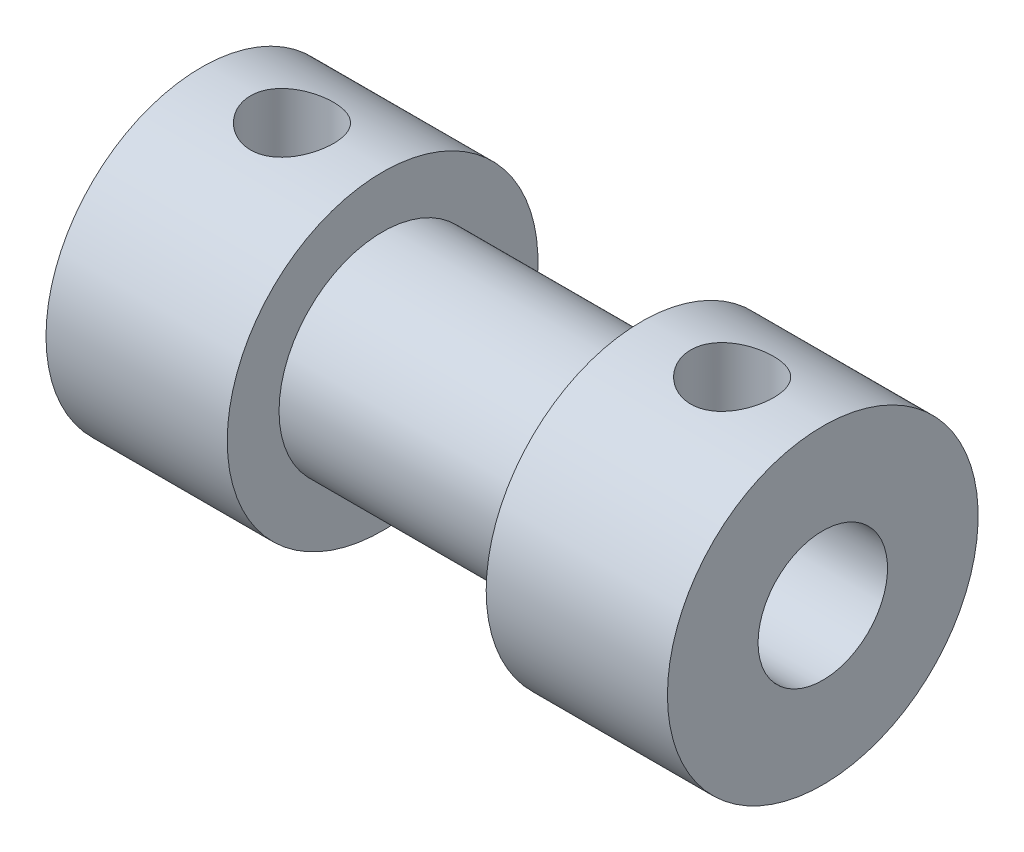
SolidWorks part; units mm, degrees
material "ABS"
ref_plane "Front Plane" through (0, 0, 0) normal (0, 0, 1) x (1, 0, 0)
ref_plane "Top Plane" through (0, 0, 0) normal (0, 1, 0) x (1, 0, 0)
ref_plane "Right Plane" through (0, 0, 0) normal (1, 0, 0) x (0, 0, -1)
sketch "Sketch1" plane through (0, 0, 0) normal (0, 0, 1) x (1, 0, 0)
  line L0 (0, -2.5) -> (0, -6)
  line L1 (0, -6) -> (7, -6)
  line L2 (7, -6) -> (7, -4)
  line L3 (7, -4) -> (17, -4)
  line L4 (17, -4) -> (17, -6)
  line L5 (17, -6) -> (24, -6)
  line L6 (24, -6) -> (24, -2.5)
  line L13 (0, 0) -> (0, -2.5) construction
  line L14 (0, -2.5) -> (24, -2.5)
  line L15 (0, 0) -> (24, 0) construction
  line L16 (24, 0) -> (24, -2.5) construction
  dimension "D1" = 7
  dimension "D2" = 7
  dimension "D3" = 10
  dimension "D4" = 2.5
  dimension "D5" = 3.5
  dimension "D6" = 4
revolve "Revolve1" add sketch "Sketch1" angle 360 about L15
sketch "Sketch2" plane through (0, 0, 0) normal (0, 1, 0) x (1, 0, 0)
  line L0 (0, 0) -> (7, 0) construction
  line L1 (0, 6) -> (0, -6) construction
  line L2 (7, -6) -> (7, 6) construction
  line L3 (17, 0) -> (24, 0) construction
  line L4 (17, 6) -> (17, -6) construction
  line L5 (24, -6) -> (24, 6) construction
  circle A1 centre (3.5, 0) radius 1.6
  circle A2 centre (20.5, 0) radius 1.6
  dimension "D1" = 3.2
extrude "Cut-Extrude1" cut sketch "Sketch2" along normal blind 10
